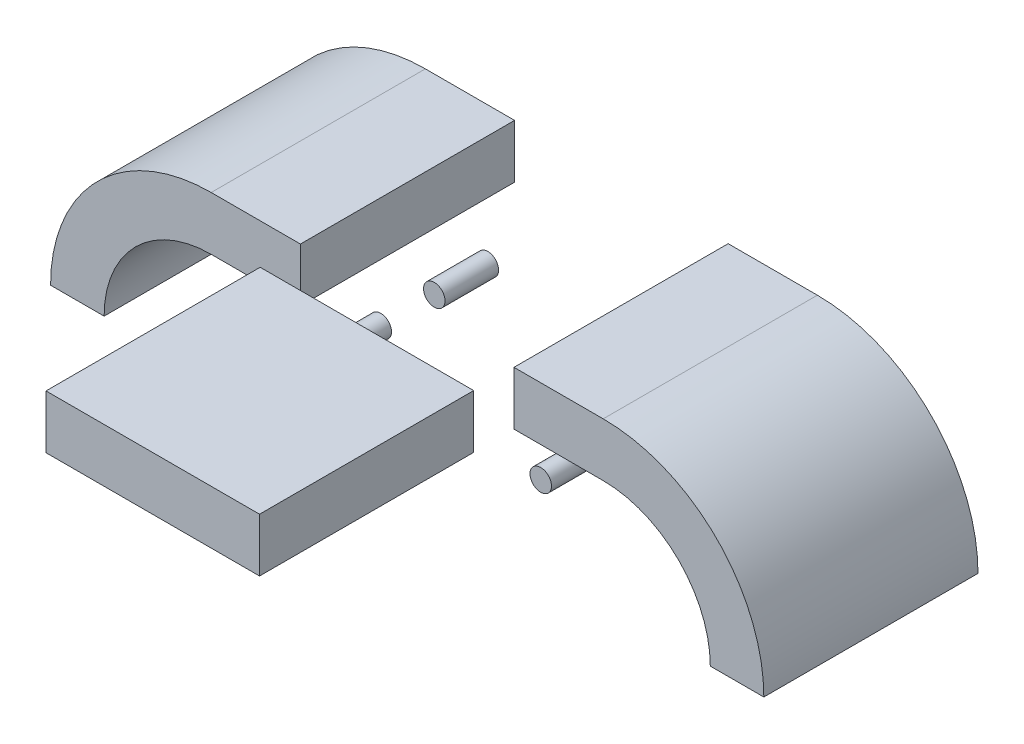
SolidWorks part; units mm, degrees
ref_plane "前视基准面" through (0, 0, 0) normal (0, 0, 1) x (1, 0, 0)
ref_plane "上视基准面" through (0, 0, 0) normal (0, 1, 0) x (1, 0, 0)
ref_plane "右视基准面" through (0, 0, 0) normal (1, 0, 0) x (0, 0, -1)
sketch "草图2" plane through (0, 0, 0) normal (0, 0, 1) x (1, 0, 0)
  line L1 (23.9298, 0) -> (43.9298, 0)
  line L2 (23.9298, 0) -> (23.9298, 12)
  line L3 (23.9298, 12) -> (43.9298, 12)
  line L4 (43.9298, 0) -> (43.9298, 12)
  dimension "D1" = 12
  dimension "D2" = 20
extrude "凸台-拉伸2" add sketch "草图2" along normal blind 48
sketch "草图9" plane through (0, 0, 48) normal (0, 0, 1) x (1, 0, 0)
  line L0 (67.9298, -24) -> (79.9298, -24)
  line L1 (43.9298, 12) -> (23.9298, 12) construction
  line L2 (23.9298, 0) -> (43.9298, 0) construction
  line L7 (23.9298, 12) -> (23.9298, 0)
  line L8 (23.9298, 0) -> (43.9298, 0)
  line L9 (43.9298, 0) -> (43.9298, 12)
  line L10 (43.9298, 12) -> (23.9298, 12)
  line L13 (43.9298, 0) -> (43.9298, 12)
  arc A0 (43.9298, 12) -> (79.9298, -24) centre (43.9298, -24) cw
  arc A1 (43.9298, 0) -> (67.9298, -24) centre (43.9298, -24) cw
  dimension "D1" = 24
  dimension "D2" = 0
extrude "凸台-拉伸4" add sketch "草图9" against normal blind 48
mirror "镜向10" about plane through (0, 0, 0) normal (1, 0, 0) of bodies 109
sketch "草图13" plane through (0, 0, 0) normal (0, 1, 0) x (1, 0, 0)
  line L1 (-23.9298, -105.0246) -> (23.9298, -105.0246)
  line L2 (-23.9298, -105.0246) -> (-23.9298, -57.0246)
  line L3 (-23.9298, -57.0246) -> (23.9298, -57.0246)
  line L4 (23.9298, -105.0246) -> (23.9298, -57.0246)
  line L5 (-23.9298, -48) -> (-23.9298, 0) construction
  line L6 (23.9298, -48) -> (23.9298, 0) construction
extrude "凸台-拉伸5" add sketch "草图13" along normal blind 12 separate body
sketch "草图15" plane through (0, 0, 0) normal (0, 0, 1) x (1, 0, 0)
  line L1 (-23.9298, 12) -> (-23.9298, 0) construction
  circle A0 centre (-23.9298, -12.8509) radius 2.4099
extrude "凸台-拉伸6" add sketch "草图15" along normal blind 12 from offset 6 separate body
ref_plane "基准面1" through (0, 0, 24) normal (0, 0, 1) x (1, 0, 0)
mirror "镜向11" about plane through (0, 0, 24) normal (0, 0, 1) of bodies 118
mirror "镜向13" about plane through (0, 0, 0) normal (1, 0, 0) of bodies 118 119
